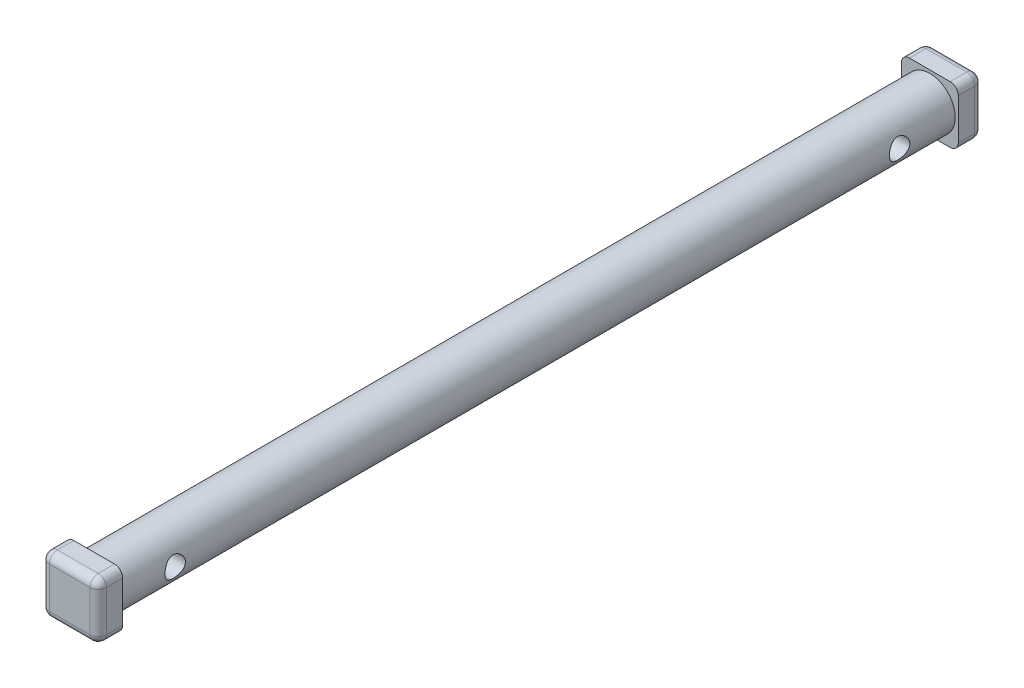
SolidWorks part; units mm, degrees
ref_plane "Front Plane" through (0, 0, 0) normal (0, 0, 1) x (1, 0, 0)
ref_plane "Top Plane" through (0, 0, 0) normal (0, 1, 0) x (1, 0, 0)
ref_plane "Right Plane" through (0, 0, 0) normal (1, 0, 0) x (0, 0, -1)
sketch "Sketch2" plane through (0, 0, 0) normal (0, 0, 1) x (1, 0, 0)
  circle A0 centre (0, 0) radius 3.9624
  dimension "D1" = 7.9248
extrude "Boss-Extrude1" add sketch "Sketch2" along normal blind 130.175
sketch "Sketch3" plane through (0, 0, 0) normal (0, 1, 0) x (1, 0, 0)
  line L0 (3.9624, 0) -> (-3.9624, 0) construction
  line L1 (7.7844, -7.0739) -> (-8.5439, -7.0739)
  line L2 (7.7844, -7.0739) -> (7.7844, -8.6614)
  line L3 (7.7844, -8.6614) -> (-8.5439, -8.6614)
  line L4 (-8.5439, -7.0739) -> (-8.5439, -8.6614)
  dimension "D1" = 1.5875
  dimension "D2" = 8.6614
revolve "Cut-Revolve2" cut sketch "Sketch3" angle 360 about L3
sketch "Sketch5" plane through (0, 0, 0) normal (1, 0, 0) x (0, 0, -1)
  line L0 (0, 3.9624) -> (-130.175, 3.9624) construction
  line L1 (-123.1011, 3.9624) -> (-121.5136, 3.9624)
  line L2 (-123.1011, 3.9624) -> (-123.1011, -3.9624)
  line L3 (-123.1011, -3.9624) -> (-121.5136, -3.9624)
  line L4 (-121.5136, 3.9624) -> (-121.5136, -3.9624)
  line L5 (-130.175, -3.9624) -> (0, -3.9624) construction
  line L6 (-130.175, 3.9624) -> (-130.175, -3.9624) construction
  dimension "D1" = 1.5875
  dimension "D2" = 8.6614
sketch "Sketch6" plane through (0, 0, 0) normal (0, 1, 0) x (1, 0, 0)
  line L0 (-3.9624, -10.2489) -> (-3.9624, -130.175) construction
  line L1 (-3.9624, -121.5136) -> (3.9624, -121.5136)
  line L2 (-3.9624, -121.5136) -> (-3.9624, -123.1011)
  line L3 (-3.9624, -123.1011) -> (3.9624, -123.1011)
  line L4 (3.9624, -121.5136) -> (3.9624, -123.1011)
  line L5 (3.9624, -130.175) -> (3.9624, -10.2489) construction
  line L6 (-3.9624, -130.175) -> (3.9624, -130.175) construction
  dimension "D1" = 1.5875
  dimension "D2" = 8.6614
revolve "Cut-Revolve4" cut sketch "Sketch6" angle 360 about L1
sketch "Sketch7" plane through (0, 0, 130.175) normal (0, 0, 1) x (1, 0, 0)
  line L1 (-4.445, -4.445) -> (4.445, -4.445)
  line L2 (-4.445, -4.445) -> (-4.445, 4.445)
  line L3 (-4.445, 4.445) -> (4.445, 4.445)
  line L4 (4.445, -4.445) -> (4.445, 4.445)
  line L5 (-4.445, -4.445) -> (4.445, 4.445) construction
  line L6 (-4.445, 4.445) -> (4.445, -4.445) construction
  point P0 (0, 0)
  dimension "D1" = 8.89
  dimension "D2" = 8.89
extrude "Boss-Extrude2" add sketch "Sketch7" along normal blind 3.81
sketch "Sketch8" plane through (0, 0, 0) normal (0, 0, -1) x (-1, 0, 0)
  line L1 (-4.445, -4.445) -> (4.445, -4.445)
  line L2 (-4.445, -4.445) -> (-4.445, 4.445)
  line L3 (-4.445, 4.445) -> (4.445, 4.445)
  line L4 (4.445, -4.445) -> (4.445, 4.445)
  line L5 (-4.445, -4.445) -> (4.445, 4.445) construction
  line L6 (-4.445, 4.445) -> (4.445, -4.445) construction
  point P0 (0, 0)
extrude "Boss-Extrude3" add sketch "Sketch8" along normal blind 3.81
fillet "Fillet1" radius 1.27 1 edges at (0, 4.445, -3.81)
fillet "Fillet2" radius 1.27 9 edges at (4.445, 4.445, -1.27) (4.445, 4.073, -3.438) (-4.445, 4.445, -1.27) (-4.445, 4.073, -3.438) (-4.445, -4.445, -1.905) (4.445, -4.445, -1.905) (4.445, -0.635, -3.81) (-4.445, -0.635, -3.81) (0, -4.445, -3.81)
fillet "Fillet3" radius 1.27 8 edges at (0, 4.445, 133.985) (4.445, 4.445, 132.08) (4.445, 0, 133.985) (4.445, -4.445, 132.08) (0, -4.445, 133.985) (-4.445, -4.445, 132.08) (-4.445, 4.445, 132.08) (-4.445, 0, 133.985)
